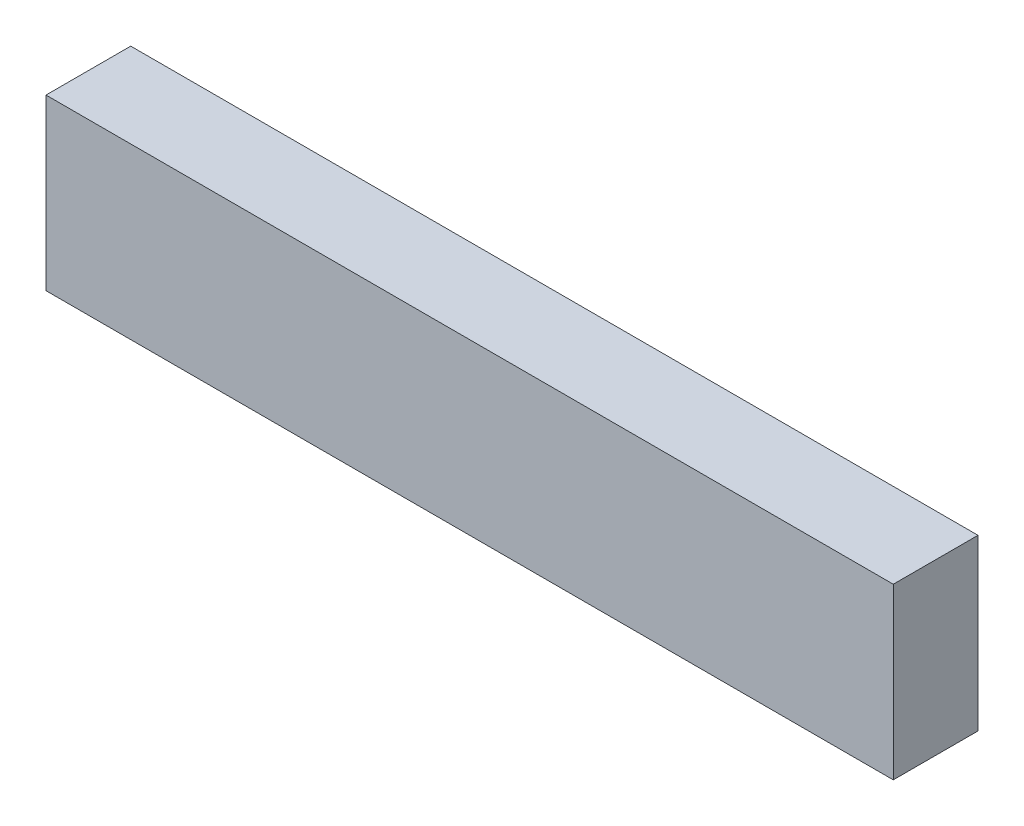
SolidWorks part; units mm, degrees
ref_plane "Спереди" through (0, 0, 0) normal (0, 0, 1) x (1, 0, 0)
ref_plane "Сверху" through (0, 0, 0) normal (0, 1, 0) x (1, 0, 0)
ref_plane "Справа" through (0, 0, 0) normal (1, 0, 0) x (0, 0, -1)
sketch "Эскиз2" plane through (0, 0, 0) normal (1, 0, 0) x (0, 0, -1)
  line L1 (5, -10) -> (-5, -10)
  line L2 (5, -10) -> (5, 10)
  line L3 (5, 10) -> (-5, 10)
  line L4 (-5, -10) -> (-5, 10)
  line L5 (5, -10) -> (-5, 10) construction
  line L6 (5, 10) -> (-5, -10) construction
  point P0 (0, 0)
  dimension "D1" = 10
  dimension "D2" = 20
extrude "Бобышка-Вытянуть1" add sketch "Эскиз2" along normal blind 100
